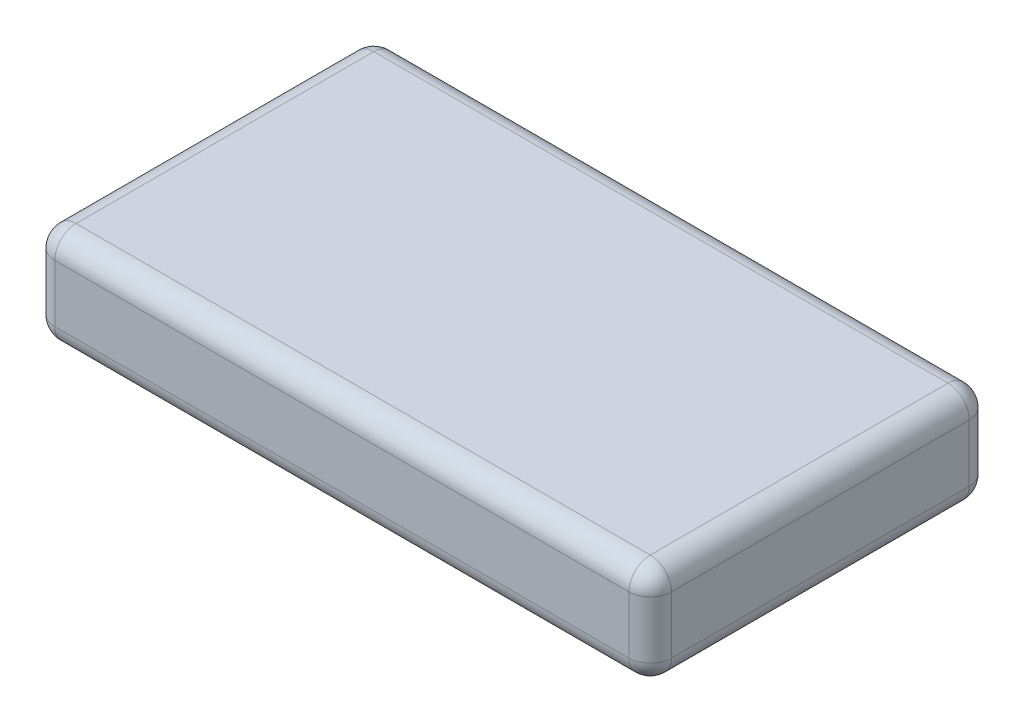
SolidWorks part; units mm, degrees
ref_plane "Front Plane" through (0, 0, 0) normal (0, 0, 1) x (1, 0, 0)
ref_plane "Top Plane" through (0, 0, 0) normal (0, 1, 0) x (1, 0, 0)
ref_plane "Right Plane" through (0, 0, 0) normal (1, 0, 0) x (0, 0, -1)
sketch "Sketch1" plane through (0, 0, 0) normal (0, 1, 0) x (1, 0, 0)
  line L1 (-29, 16) -> (29, 16)
  line L2 (-29, 16) -> (-29, -16)
  line L3 (-29, -16) -> (29, -16)
  line L4 (29, 16) -> (29, -16)
  line L5 (-29, 16) -> (29, -16) construction
  line L6 (-29, -16) -> (29, 16) construction
  point P0 (0, 0)
  dimension "D1" = 32
  dimension "D2" = 58
extrude "Boss-Extrude1" add sketch "Sketch1" along normal blind 9.4
fillet "Fillet1" radius 2 12 edges at (29, 4.7, -16) (-29, 4.7, -16) (0, 0, -16) (-29, 0, 0) (29, 0, 0) (-29, 4.7, 16) (29, 4.7, 16) (0, 0, 16) (0, 9.4, 16) (-29, 9.4, 0) (0, 9.4, -16) (29, 9.4, 0)
